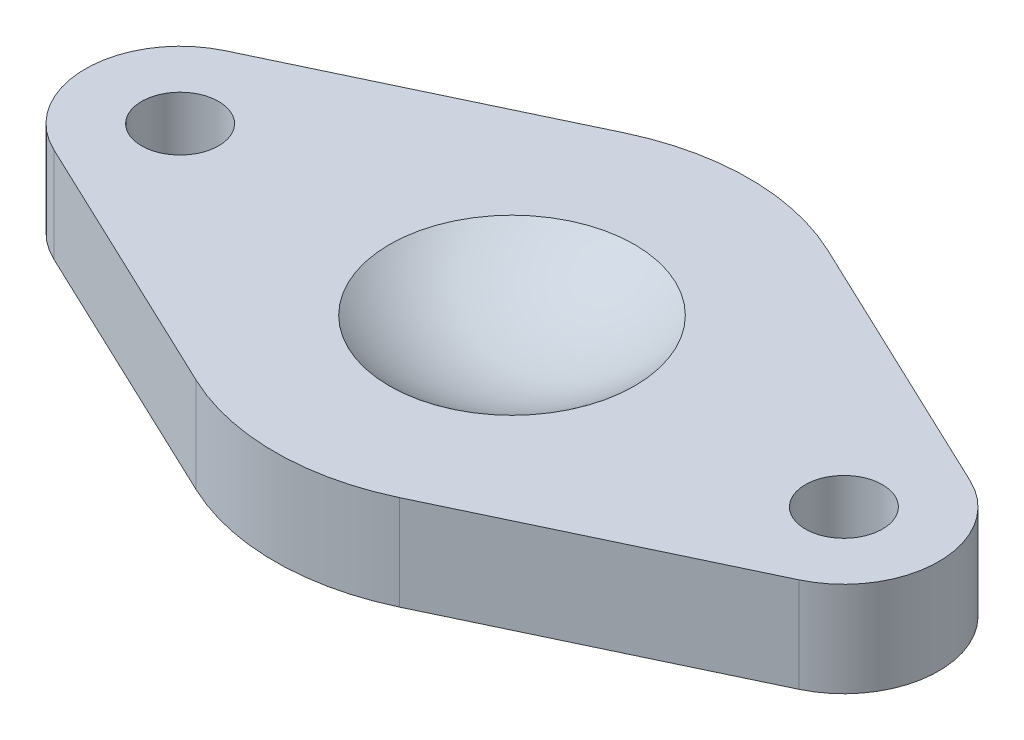
SolidWorks part; units mm, degrees
ref_plane "Front" through (0, 0, 0) normal (0, 0, 1) x (1, 0, 0)
ref_plane "Top" through (0, 0, 0) normal (0, 1, 0) x (1, 0, 0)
ref_plane "Right" through (0, 0, 0) normal (1, 0, 0) x (0, 0, -1)
sketch "Croquis1" plane through (0, 0, 0) normal (0, 1, 0) x (1, 0, 0)
  line L0 (-1000, 0) -> (49000, 0) construction
  line L1 (0, -1000) -> (0, 49000) construction
  line L2 (8.15, -1000) -> (8.15, 49000) construction
  line L3 (-8.15, -1000) -> (-8.15, 49000) construction
  line L4 (-18, 0) -> (18, 0)
  line L5 (-18, 0) -> (-18, 20.3)
  line L6 (-18, 20.3) -> (18, 20.3)
  line L7 (18, 0) -> (18, 20.3)
  line L8 (-1000, 10.15) -> (49000, 10.15) construction
  line L9 (18, -1000) -> (18, 49000) construction
  line L10 (-18, -1000) -> (-18, 49000) construction
  circle A1 centre (0, 10.15) radius 8.15 construction
  circle A5 centre (-14, 10.15) radius 1.625
  circle A6 centre (14, 10.15) radius 1.625
  point P14 (0, 0)
  point P17 (0, 20.3)
  point P19 (18, 0)
  point P22 (18, 20.3)
  point P25 (-18, 0)
  point P28 (-18, 20.3)
  dimension "D3" = 10.15
  dimension "D7" = 3.25
  dimension "D8" = 4
  dimension "D9" = 18
  dimension "D4" = 20.3
  dimension "D1" = 8.15
  dimension "D2" = 8.15
  dimension "D10" = 18
extrude "Saliente-Extruir1" add sketch "Croquis1" along normal blind 4
ref_plane "Plano1" through (0, 0, -10.15) normal (0, 0, 1) x (1, 0, 0)
sketch "Croquis2" plane through (0, 0, -10.15) normal (0, 0, 1) x (1, 0, 0)
  line L0 (0, -1000) -> (0, 49000) construction
  line L1 (-1000, 0) -> (49000, 0) construction
  line L2 (-1000, 4) -> (49000, 4) construction
  line L3 (0, 18.45) -> (0, 2.15)
  circle A0 centre (0, 10.3) radius 8.15 construction
  arc A1 (0, 2.15) -> (0, 18.45) centre (0, 10.3) cw
  dimension "D2" = 16.3
  dimension "D3" = 10.3
  dimension "D4" = 8.15
  dimension "D1" = 4
revolve "Cortar-Revolución1" cut sketch "Croquis2" angle 360 about L0
sketch "Croquis3" plane through (0, 4, 0) normal (0, 1, 0) x (1, 0, 0)
  line L0 (0, -1000) -> (0, 49000) construction
  line L1 (-15.7143, 13.764) -> (-4.2857, 19.1851)
  line L2 (-1000, 10.15) -> (49000, 10.15) construction
  line L3 (-15.7143, 6.536) -> (-4.2857, 1.1149)
  line L4 (15.7143, 6.536) -> (4.2857, 1.1149)
  line L6 (15.7143, 13.764) -> (4.2857, 19.1851)
  line L7 (18, 0) -> (-18, 0)
  line L8 (18, 0) -> (18, 20.3)
  line L9 (18, 20.3) -> (-18, 20.3)
  line L10 (-18, 0) -> (-18, 20.3)
  line L11 (18, 0) -> (-18, 20.3) construction
  line L12 (18, 20.3) -> (-18, 0) construction
  arc A0 (-15.7143, 13.764) -> (-15.7143, 6.536) centre (-14, 10.15) ccw
  arc A1 (15.7143, 13.764) -> (15.7143, 6.536) centre (14, 10.15) cw
  arc A2 (4.2857, 19.1851) -> (-4.2857, 19.1851) centre (0, 10.15) ccw
  arc A3 (-4.2857, 1.1149) -> (4.2857, 1.1149) centre (0, 10.15) ccw
  line M14 (-18, 20.3) -> (-18, 0)
  line M15 (-18, 0) -> (18, 0)
  line M16 (18, 0) -> (18, 20.3)
  line M17 (18, 20.3) -> (-18, 20.3)
  dimension "D1" = 8
  dimension "D2" = 20
extrude "Cortar-Extruir2" cut sketch "Croquis3" against normal through all contours A2 L6 A1 L8 A0 L1 M17 M14 | A3 L3 A0 L10 A1 L4 M15 M16
